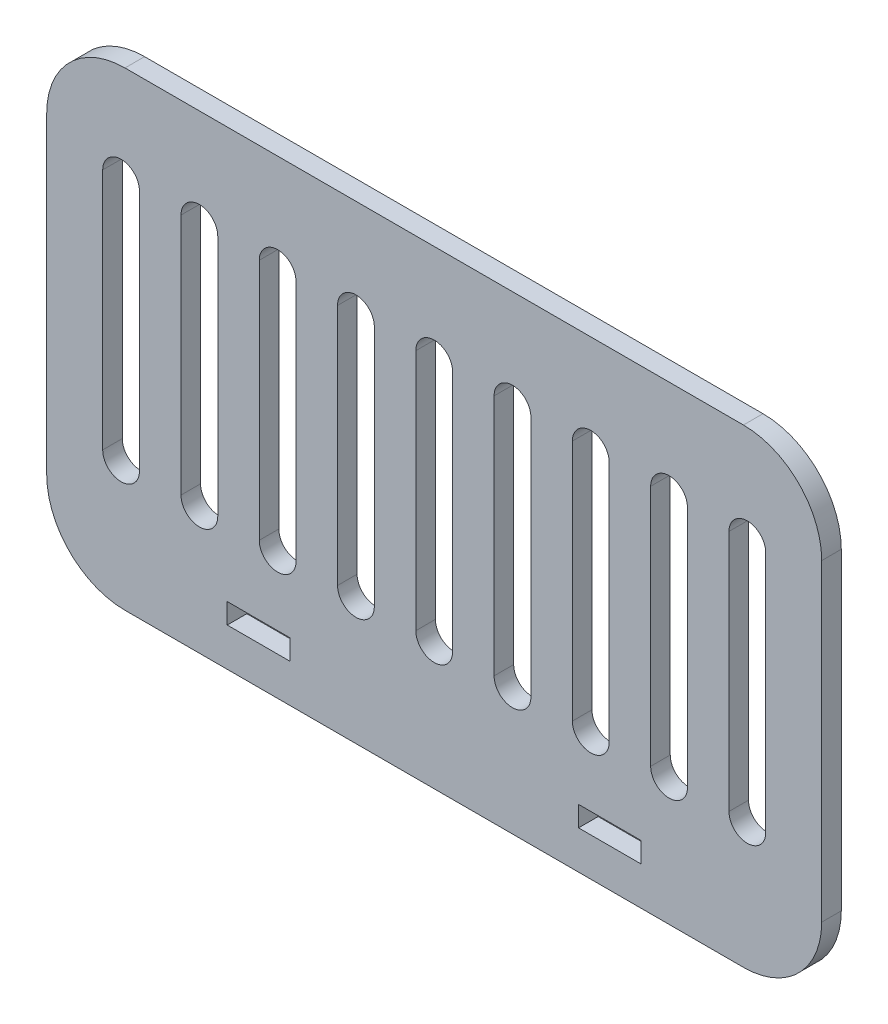
SolidWorks part; units mm, degrees
ref_plane "Front" through (0, 0, 0) normal (0, 0, 1) x (1, 0, 0)
ref_plane "Top" through (0, 0, 0) normal (0, 1, 0) x (1, 0, 0)
ref_plane "Right" through (0, 0, 0) normal (1, 0, 0) x (0, 0, -1)
sketch "Sketch1" plane through (0, 0, 0) normal (0, 0, 1) x (1, 0, 0)
  line L0 (0, 0) -> (0, -38.1) construction
  line L1 (-62.865, 38.1) -> (62.865, 38.1)
  line L2 (-62.865, 38.1) -> (-62.865, -38.1)
  line L3 (-62.865, -38.1) -> (62.865, -38.1)
  line L4 (62.865, 38.1) -> (62.865, -38.1)
  line L5 (-62.865, 38.1) -> (62.865, -38.1) construction
  line L6 (-62.865, -38.1) -> (62.865, 38.1) construction
  line L7 (-33.5788, -28.575) -> (-23.4188, -28.575)
  line L8 (-33.5788, -28.575) -> (-33.5788, -31.877)
  line L9 (-33.5788, -31.877) -> (-23.4188, -31.877)
  line L10 (-23.4188, -28.575) -> (-23.4188, -31.877)
  line L11 (-33.5788, -28.575) -> (-23.4188, -31.877) construction
  line L12 (-33.5788, -31.877) -> (-23.4188, -28.575) construction
  line L13 (33.5788, -31.877) -> (23.4188, -28.575) construction
  line L14 (33.5788, -28.575) -> (23.4188, -31.877) construction
  line L15 (23.4188, -28.575) -> (23.4188, -31.877)
  line L16 (33.5788, -31.877) -> (23.4188, -31.877)
  line L17 (33.5788, -28.575) -> (33.5788, -31.877)
  line L18 (33.5788, -28.575) -> (23.4188, -28.575)
  point P0 (0, 0)
  point P6 (-28.4988, -30.226)
  point P17 (28.4988, -30.226)
  dimension "D1" = 125.73
  dimension "D2" = 76.2
  dimension "D3" = 56.9976
  dimension "D4" = 3.302
  dimension "D5" = 10.16
  dimension "D6" = 7.874
extrude "Boss-Extrude1" add sketch "Sketch1" along normal blind 3.175
sketch "Sketch2" plane through (0, 0, 3.175) normal (0, 0, 1) x (1, 0, 0)
  line L0 (-62.865, 38.1) -> (62.865, 38.1) construction
  line L1 (59.69, 38.1) -> (-59.69, 38.1)
  line L4 (-59.69, -22.225) -> (59.69, -22.225)
  line L6 (0, 0) -> (0, -38.1) construction
  line L7 (59.69, -38.1) -> (59.69, 34.925)
  line L8 (59.69, 34.925) -> (-59.69, 34.925)
  line L9 (-59.69, 34.925) -> (-59.69, -38.1)
  line L10 (59.69, -22.225) -> (59.69, 38.1)
  line L12 (-59.69, 38.1) -> (-59.69, -22.225)
  arc A22 (-43.18, -22.225) -> (-59.69, 18.4745) centre (-101.6, -22.225) ccw
  arc A23 (-35.2281, -22.225) -> (-59.69, 23.2816) centre (-101.6, -28.575) ccw
  arc A24 (-17.78, -22.225) -> (-59.69, 33.8135) centre (-76.2, -22.225) ccw
  arc A25 (-9.8281, -22.225) -> (-59.69, 36.0236) centre (-76.2, -28.575) ccw
  arc A26 (7.62, -22.225) -> (-59.69, 35.5146) centre (-50.8, -22.225) ccw
  arc A27 (15.5719, -22.225) -> (-59.69, 37.5047) centre (-50.8, -28.575) ccw
  arc A28 (33.02, -22.225) -> (-59.69, 25.0729) centre (-25.4, -22.225) ccw
  arc A29 (40.9719, -22.225) -> (-59.69, 28.6067) centre (-25.4, -28.575) ccw
  arc A30 (58.42, -22.225) -> (-58.42, -22.225) centre (0, -22.225) ccw
  arc A31 (59.69, 1.1346) -> (-59.69, 1.1346) centre (0, -28.575) ccw
  arc A32 (59.69, 25.0729) -> (-33.02, -22.225) centre (25.4, -22.225) ccw
  arc A34 (59.69, 18.4745) -> (43.18, -22.225) centre (101.6, -22.225) ccw
  arc A35 (59.69, 23.2816) -> (35.2281, -22.225) centre (101.6, -28.575) ccw
  arc A36 (59.69, 35.5146) -> (-7.62, -22.225) centre (50.8, -22.225) ccw
  arc A37 (59.69, 33.8135) -> (17.78, -22.225) centre (76.2, -22.225) ccw
  arc A38 (59.69, 37.5047) -> (-15.5719, -22.225) centre (50.8, -28.575) ccw
  arc A39 (59.69, 36.0236) -> (9.8281, -22.225) centre (76.2, -28.575) ccw
  arc A40 (59.69, 28.6067) -> (-40.9719, -22.225) centre (25.4, -28.575) ccw
  dimension "D1" = 3.175
  dimension "D3" = 6.35
extrude "Cut-Extrude1" [suppressed] cut sketch "Sketch2" against normal through all contours A38 A26 A32 A25 | A31 A22 L12 | A22 A30 L4 | A40 A24 A30 A23 | A24 A32 L4 | A39 A28 A36 A27 | A26 A36 L4 | A28 A37 L4 | A30 A37 A29 A35 | A30 A34 L4 | L10 A34 A31 | A31 A24 A28 L12 A23 | A31 A26 A28 A25 | A29 A24 L12 | A40 A28 A30 A27 | A40 A26 A30 A25 | A38 A28 A32 A27 | A38 A30 A32 A29 | A39 A30 A36 A29 | A39 A32 A36 A31 | A32 A37 A31 A35 L10 | A40 L10 A37
fillet "Fillet1" radius 12.7 4 edges at (62.865, 38.1, 1.5875) (-62.865, 38.1, 1.5875) (62.865, -38.1, 1.5875) (-62.865, -38.1, 1.5875)
sketch "Sketch5" plane through (0, 0, 3.175) normal (0, 0, 1) x (1, 0, 0)
  line L0 (0, 21.9698) -> (0, -17.3721) construction
  line L1 (0, 0) -> (0, -38.1) construction
  line L2 (2.9841, 21.9698) -> (2.9841, -17.3721)
  line L3 (-2.9841, 21.9698) -> (-2.9841, -17.3721)
  line L4 (12.7, 21.9698) -> (12.7, -17.3721) construction
  line L5 (15.6841, 21.9698) -> (15.6841, -17.3721)
  line L6 (9.7159, 21.9698) -> (9.7159, -17.3721)
  line L7 (25.4, 21.9698) -> (25.4, -17.3721) construction
  line L8 (28.3841, 21.9698) -> (28.3841, -17.3721)
  line L9 (22.4159, 21.9698) -> (22.4159, -17.3721)
  line L10 (38.1, 21.9698) -> (38.1, -17.3721) construction
  line L11 (41.0841, 21.9698) -> (41.0841, -17.3721)
  line L12 (35.1159, 21.9698) -> (35.1159, -17.3721)
  line L13 (50.8, 21.9698) -> (50.8, -17.3721) construction
  line L14 (53.7841, 21.9698) -> (53.7841, -17.3721)
  line L15 (47.8159, 21.9698) -> (47.8159, -17.3721)
  line L16 (-12.7, 21.9698) -> (-12.7, -17.3721) construction
  line L17 (-9.7159, 21.9698) -> (-9.7159, -17.3721)
  line L18 (-15.6841, 21.9698) -> (-15.6841, -17.3721)
  line L19 (-25.4, 21.9698) -> (-25.4, -17.3721) construction
  line L20 (-22.4159, 21.9698) -> (-22.4159, -17.3721)
  line L21 (-28.3841, 21.9698) -> (-28.3841, -17.3721)
  line L22 (-38.1, 21.9698) -> (-38.1, -17.3721) construction
  line L23 (-35.1159, 21.9698) -> (-35.1159, -17.3721)
  line L24 (-41.0841, 21.9698) -> (-41.0841, -17.3721)
  line L25 (-50.8, 21.9698) -> (-50.8, -17.3721) construction
  line L26 (-47.8159, 21.9698) -> (-47.8159, -17.3721)
  line L27 (-53.7841, 21.9698) -> (-53.7841, -17.3721)
  arc A0 (2.9841, 21.9698) -> (-2.9841, 21.9698) centre (0, 21.9698) ccw
  arc A1 (-2.9841, -17.3721) -> (2.9841, -17.3721) centre (0, -17.3721) ccw
  arc A2 (15.6841, 21.9698) -> (9.7159, 21.9698) centre (12.7, 21.9698) ccw
  arc A3 (9.7159, -17.3721) -> (15.6841, -17.3721) centre (12.7, -17.3721) ccw
  arc A4 (28.3841, 21.9698) -> (22.4159, 21.9698) centre (25.4, 21.9698) ccw
  arc A5 (22.4159, -17.3721) -> (28.3841, -17.3721) centre (25.4, -17.3721) ccw
  arc A6 (41.0841, 21.9698) -> (35.1159, 21.9698) centre (38.1, 21.9698) ccw
  arc A7 (35.1159, -17.3721) -> (41.0841, -17.3721) centre (38.1, -17.3721) ccw
  arc A8 (53.7841, 21.9698) -> (47.8159, 21.9698) centre (50.8, 21.9698) ccw
  arc A9 (47.8159, -17.3721) -> (53.7841, -17.3721) centre (50.8, -17.3721) ccw
  arc A10 (-9.7159, 21.9698) -> (-15.6841, 21.9698) centre (-12.7, 21.9698) ccw
  arc A11 (-15.6841, -17.3721) -> (-9.7159, -17.3721) centre (-12.7, -17.3721) ccw
  arc A12 (-22.4159, 21.9698) -> (-28.3841, 21.9698) centre (-25.4, 21.9698) ccw
  arc A13 (-28.3841, -17.3721) -> (-22.4159, -17.3721) centre (-25.4, -17.3721) ccw
  arc A14 (-35.1159, 21.9698) -> (-41.0841, 21.9698) centre (-38.1, 21.9698) ccw
  arc A15 (-41.0841, -17.3721) -> (-35.1159, -17.3721) centre (-38.1, -17.3721) ccw
  arc A16 (-47.8159, 21.9698) -> (-53.7841, 21.9698) centre (-50.8, 21.9698) ccw
  arc A17 (-53.7841, -17.3721) -> (-47.8159, -17.3721) centre (-50.8, -17.3721) ccw
  point P4 (0, 2.2989)
  point P12 (12.7, 2.2989)
  point P19 (25.4, 2.2989)
  point P26 (38.1, 2.2989)
  point P33 (50.8, 2.2989)
  point P41 (-12.7, 2.2989)
  point P48 (-25.4, 2.2989)
  point P55 (-38.1, 2.2989)
  point P62 (-50.8, 2.2989)
extrude "Cut-Extrude2" cut sketch "Sketch5" against normal through all
